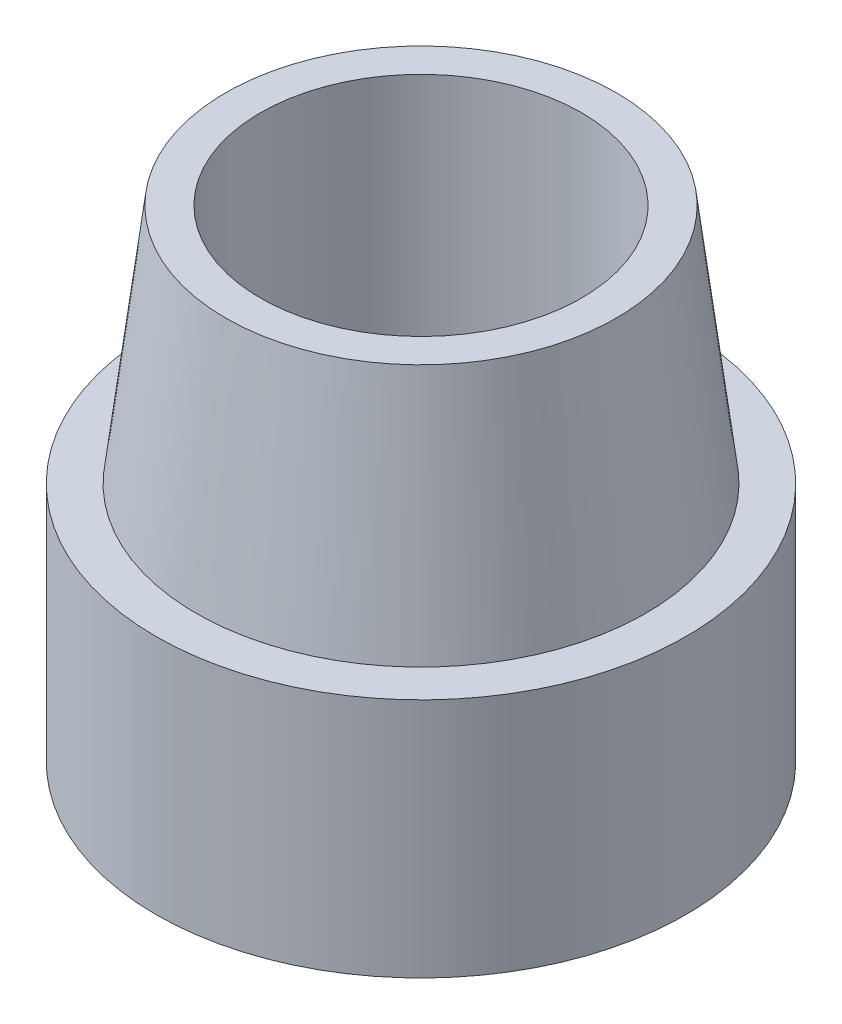
SolidWorks part; units mm, degrees
ref_plane "Front Plane" through (0, 0, 0) normal (0, 0, 1) x (1, 0, 0)
ref_plane "Top Plane" through (0, 0, 0) normal (0, 1, 0) x (1, 0, 0)
ref_plane "Right Plane" through (0, 0, 0) normal (1, 0, 0) x (0, 0, -1)
sketch "Sketch1" plane through (0, 0, 0) normal (0, 0, 1) x (1, 0, 0)
  line L0 (0, 0) -> (0, 30) construction
  line L1 (10, 0) -> (10, 30)
  line L2 (10, 0) -> (16.5, 0)
  line L3 (16.5, 0) -> (16.5, 15)
  line L4 (16.5, 15) -> (14.0018, 15)
  line L5 (14.0018, 15) -> (12.16, 30)
  line L6 (12.16, 30) -> (10, 30)
  dimension "D1" = 30
  dimension "D2" = 20
  dimension "D3" = 15
  dimension "D4" = 33
  dimension "D5" = 83
  dimension "D6" = 24.32
revolve "Revolve1" add sketch "Sketch1" angle 360 about L0
